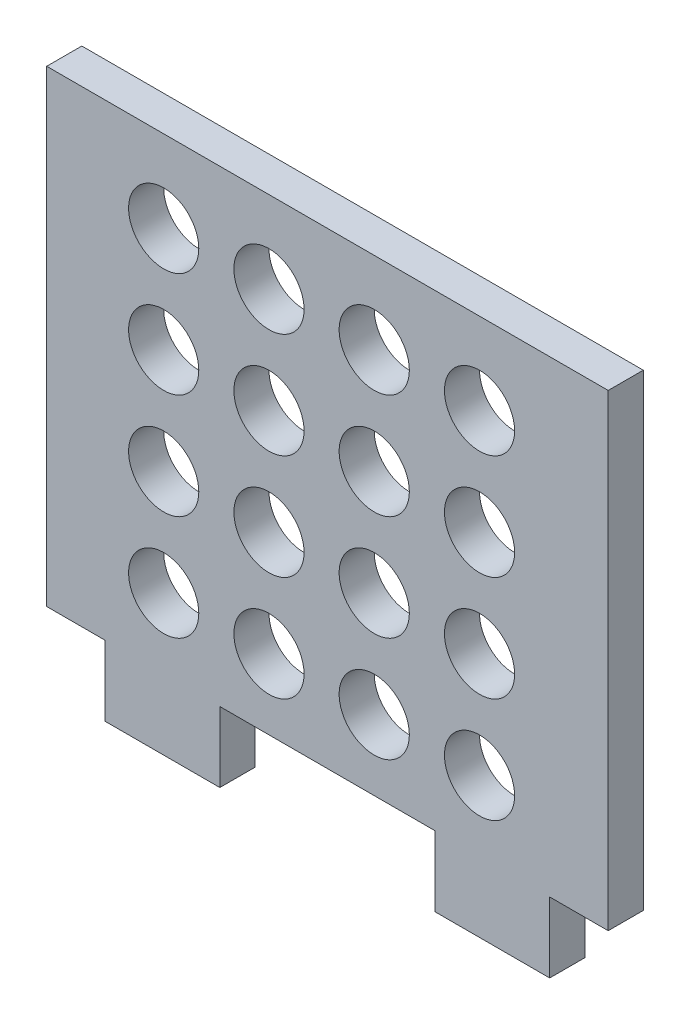
SolidWorks part; units mm, degrees
ref_plane "Plan de face" through (0, 0, 0) normal (0, 0, 1) x (1, 0, 0)
ref_plane "Plan de dessus" through (0, 0, 0) normal (0, 1, 0) x (1, 0, 0)
ref_plane "Plan de droite" through (0, 0, 0) normal (1, 0, 0) x (0, 0, -1)
sketch "Esquisse1" plane through (0, 0, 0) normal (0, 0, 1) x (1, 0, 0)
  line L0 (-12, 0) -> (12, 0)
  line L1 (12, 0) -> (12, 20)
  line L2 (12, 20) -> (-12, 20)
  line L3 (-12, 20) -> (-12, 0)
  point P4 (0, 0)
  dimension "D1" = 20
  dimension "D2" = 24
extrude "Boss.-Extru.1" add sketch "Esquisse1" along normal blind 1.5
sketch "Esquisse2" plane through (0, 0, 0) normal (0, 0, 1) x (1, 0, 0)
  line L0 (4.6, 0) -> (4.6, -3)
  line L1 (-12, 0) -> (12, 0) construction
  line L2 (4.6, -3) -> (9.5, -3)
  line L3 (9.5, -3) -> (9.5, 0)
  line L4 (9.5, 0) -> (4.6, 0)
  line L5 (12, 0) -> (12, 20) construction
  line L6 (0, -4.7268) -> (0, 22.7867) construction
  line L7 (-9.5, -3) -> (-9.5, 0)
  line L8 (-4.6, -3) -> (-9.5, -3)
  line L9 (-4.6, 0) -> (-4.6, -3)
  line L10 (-9.5, 0) -> (-4.6, 0)
  dimension "D1" = 4.9
  dimension "D2" = 2.5
  dimension "D3" = 3
extrude "Boss.-Extru.2" add sketch "Esquisse2" along normal blind 1.5
sketch "Esquisse3" plane through (0, 0, 1.5) normal (0, 0, 1) x (1, 0, 0)
  line L0 (-12, 20) -> (-12, 0) construction
  line L1 (-4.6, 0) -> (4.6, 0) construction
  circle A0 centre (-7, 3) radius 1.5
  circle A1 centre (-2.5, 3) radius 1.5
  circle A2 centre (2, 3) radius 1.5
  circle A3 centre (6.5, 3) radius 1.5
  circle A4 centre (-2.5, 7.5) radius 1.5
  circle A5 centre (2, 7.5) radius 1.5
  circle A6 centre (6.5, 7.5) radius 1.5
  circle A7 centre (-2.5, 12) radius 1.5
  circle A8 centre (2, 12) radius 1.5
  circle A9 centre (6.5, 12) radius 1.5
  circle A10 centre (-2.5, 16.5) radius 1.5
  circle A11 centre (2, 16.5) radius 1.5
  circle A12 centre (6.5, 16.5) radius 1.5
  circle A13 centre (-7, 7.5) radius 1.5
  circle A14 centre (-7, 12) radius 1.5
  circle A15 centre (-7, 16.5) radius 1.5
  dimension "D1" = 5
  dimension "D2" = 3
  dimension "D3" = 3
  dimension "D4" = 4
extrude "Enlèv. mat.-Extru.1" cut sketch "Esquisse3" against normal up to next
